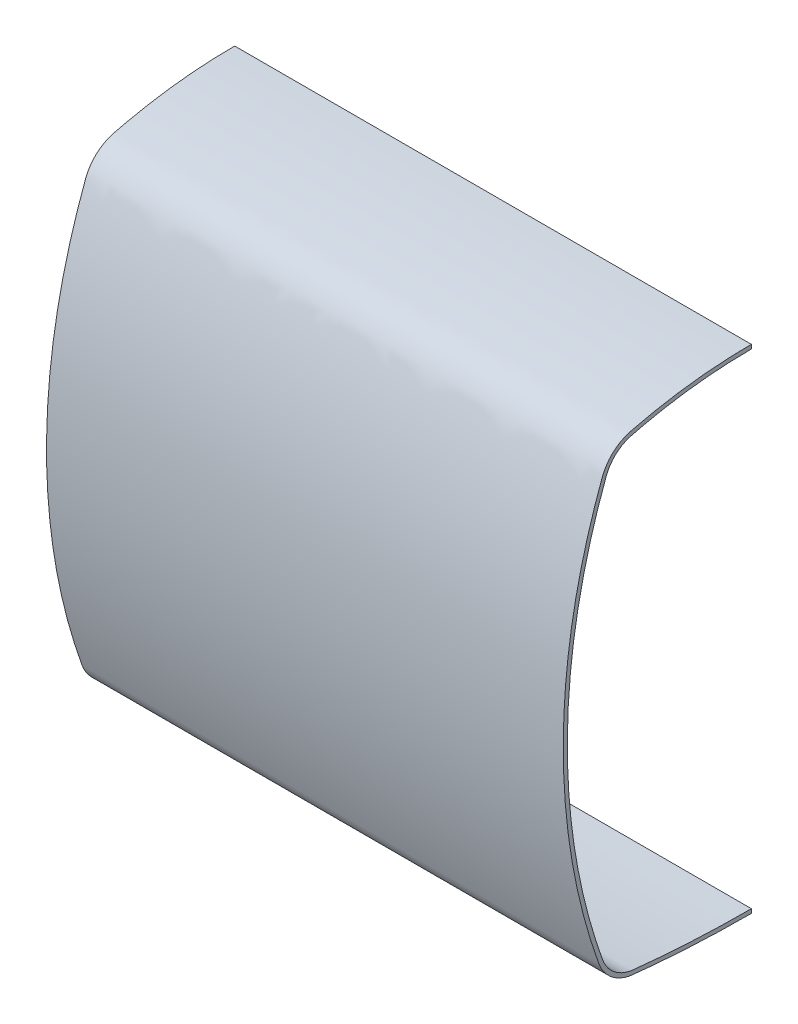
SolidWorks part; units mm, degrees
ref_plane "Front Plane" through (0, 0, 0) normal (0, 0, 1) x (1, 0, 0)
ref_plane "Top Plane" through (0, 0, 0) normal (0, 1, 0) x (1, 0, 0)
ref_plane "Right Plane" through (0, 0, 0) normal (1, 0, 0) x (0, 0, -1)
sketch "Sketch4" plane through (-245.2175, 0, 0) normal (-1, 0, 0) x (0, 0, 1)
  line L2 (-67.5, 233.8923) -> (-67.5, 231.8923)
  line L3 (-67.5, -6.3455) -> (-67.5, -8.3455)
  line L4 (-67.5, 233.8923) -> (-67.5, 231.8923)
  line L5 (-67.5, -6.3455) -> (-67.5, -8.3455)
  spline S0 degree 3 poles (1438.556, -2100.2402) (-873.6165, -475.5488) (-387.365, 299.3972) (-17.1984, 228.692) (-12.6576, 227.6897) (-8.1266, 226.5524) (-8.1092, 226.548) (-7.9319, 226.503) (-6.7443, 226.1858) (-5.5937, 225.7604) (-2.7193, 224.4334) (-0.9506, 223.251) (1.37, 221.1008) (2.0878, 220.3203) (3.3906, 218.6556) (3.9767, 217.7712) (4.7473, 216.3812) (5.1802, 215.5222) (5.5505, 214.6326) (5.7152, 214.1972) (5.7251, 214.1709) (7.4554, 209.5819) (9.06, 204.9894) (19.9636, 171.1652) (24.7754, 140.8594) (25.1771, 80.1824) (20.7669, 49.8105) (10.4386, 16.263) (9.0469, 12.073) (7.5497, 7.8792) (7.5389, 7.849) (7.3926, 7.443) (6.8573, 6.0863) (6.1793, 4.8001) (4.4911, 2.1299) (3.0868, 0.5311) (0.6314, -1.4978) (-0.2386, -2.1068) (-2.0558, -3.1763) (-3.0041, -3.6378) (-4.9622, -4.4067) (-6.4767, -4.8678) (-8.2512, -5.1848) (-8.9922, -5.2748) (-9.2233, -5.2991) (-9.2369, -5.3005) (-13.3393, -5.7303) (-17.4291, -6.1134) (-569.4844, -51.6962) (-1159.1756, 713.6096) (-1877.6478, 2288.9262) knots -2.89955 -2.89955 -2.89955 -2.89955 0.125 0.125 0.16272 0.16272 0.162842 0.162842 0.164062 0.171875 0.171875 0.1875 0.1875 0.195312 0.195312 0.203125 0.203125 0.207031 0.210205 0.210205 0.210449 0.210449 0.25 0.25 0.5 0.5 0.75 0.75 0.785889 0.785889 0.786133 0.786133 0.789062 0.796875 0.796875 0.8125 0.8125 0.820312 0.820312 0.828125 0.828125 0.835938 0.839844 0.841431 0.841431 0.841553 0.841553 0.875 0.875 5.353831 5.353831 5.353831 5.353831 only from (-67.5, 233.8923) to (-67.5, -8.3455) construction
  spline S1 degree 3 poles (-1573.5108, -2100.1852) (738.6059, -475.5313) (252.3609, 299.3964) (-117.7869, 228.6949) (-122.313, 227.6962) (-126.8734, 226.5524) (-126.9392, 226.5358) (-127.1323, 226.4858) (-128.2868, 226.1743) (-129.4063, 225.7604) (-132.2807, 224.4334) (-134.0494, 223.251) (-136.37, 221.1008) (-137.0878, 220.3203) (-138.3906, 218.6556) (-138.9767, 217.7712) (-139.7473, 216.3812) (-140.1802, 215.5222) (-140.5505, 214.6326) (-140.7152, 214.1972) (-140.7251, 214.1709) (-142.4554, 209.5819) (-144.06, 204.9894) (-154.9636, 171.1652) (-159.7754, 140.8594) (-160.1771, 80.1824) (-155.7669, 49.8105) (-145.4386, 16.263) (-144.0469, 12.073) (-142.5497, 7.8792) (-142.5389, 7.849) (-142.3926, 7.443) (-141.8573, 6.0863) (-141.1793, 4.8001) (-139.4911, 2.1299) (-138.0868, 0.5311) (-135.6314, -1.4978) (-134.7614, -2.1068) (-132.9442, -3.1763) (-131.9959, -3.6378) (-130.0378, -4.4067) (-128.5233, -4.8678) (-126.765, -5.1819) (-126.0408, -5.2708) (-125.7767, -5.2992) (-125.7184, -5.3052) (-121.601, -5.7359) (-117.5411, -6.1159) (434.4989, -51.6974) (1024.2084, 713.6501) (1742.5472, 2289.0513) knots -2.899516 -2.899516 -2.899516 -2.899516 0.125 0.125 0.162598 0.162598 0.163086 0.163086 0.164063 0.171875 0.171875 0.1875 0.1875 0.195313 0.195313 0.203125 0.203125 0.207031 0.210205 0.210205 0.210449 0.210449 0.25 0.25 0.5 0.5 0.75 0.75 0.785889 0.785889 0.786133 0.786133 0.789063 0.796875 0.796875 0.8125 0.8125 0.820313 0.820313 0.828125 0.828125 0.835938 0.839844 0.841309 0.841309 0.841797 0.841797 0.875 0.875 5.35395 5.35395 5.35395 5.35395 only from (-67.5, 233.8923) to (-67.5, -8.3455) construction
  spline S2 degree 3 poles (-67.5, 233.8923) (-52.184, 233.8923) (-32.2462, 232.0136) (-12.6576, 227.6897) (-8.1266, 226.5524) (-8.1092, 226.548) (-7.9319, 226.503) (-6.7443, 226.1858) (-5.5937, 225.7604) (-2.7193, 224.4334) (-0.9506, 223.251) (1.37, 221.1008) (2.0878, 220.3203) (3.3906, 218.6556) (3.9767, 217.7712) (4.7473, 216.3812) (5.1802, 215.5222) (5.5505, 214.6326) (5.7152, 214.1972) (5.7251, 214.1709) (7.4554, 209.5819) (9.06, 204.9894) (19.9636, 171.1652) (24.7754, 140.8594) (25.1771, 80.1824) (20.7669, 49.8105) (10.4386, 16.263) (9.0469, 12.073) (7.5497, 7.8792) (7.5389, 7.849) (7.3926, 7.443) (6.8573, 6.0863) (6.1793, 4.8001) (4.4911, 2.1299) (3.0868, 0.5311) (0.6314, -1.4978) (-0.2386, -2.1068) (-2.0558, -3.1763) (-3.0041, -3.6378) (-4.9622, -4.4067) (-6.4767, -4.8678) (-8.2512, -5.1848) (-8.9922, -5.2748) (-9.2233, -5.2991) (-9.2369, -5.3005) (-13.3393, -5.7303) (-32.7135, -7.5451) (-52.14, -8.3454) (-67.5, -8.3455) knots 0 0 0 0 0.125 0.16272 0.16272 0.162842 0.162842 0.164062 0.171875 0.171875 0.1875 0.1875 0.195312 0.195312 0.203125 0.203125 0.207031 0.210205 0.210205 0.210449 0.210449 0.25 0.25 0.5 0.5 0.75 0.75 0.785889 0.785889 0.786133 0.786133 0.789062 0.796875 0.796875 0.8125 0.8125 0.820312 0.820312 0.828125 0.828125 0.835938 0.839844 0.841431 0.841431 0.841553 0.841553 0.875 1 1 1 1
  spline S3 degree 3 poles (-67.5, 233.8923) (-82.816, 233.8923) (-102.7389, 232.015) (-122.313, 227.6962) (-126.8734, 226.5524) (-126.9392, 226.5358) (-127.1323, 226.4858) (-128.2868, 226.1743) (-129.4063, 225.7604) (-132.2807, 224.4334) (-134.0494, 223.251) (-136.37, 221.1008) (-137.0878, 220.3203) (-138.3906, 218.6556) (-138.9767, 217.7712) (-139.7473, 216.3812) (-140.1802, 215.5222) (-140.5505, 214.6326) (-140.7152, 214.1972) (-140.7251, 214.1709) (-142.4554, 209.5819) (-144.06, 204.9894) (-154.9636, 171.1652) (-159.7754, 140.8594) (-160.1771, 80.1824) (-155.7669, 49.8105) (-145.4386, 16.263) (-144.0469, 12.073) (-142.5497, 7.8792) (-142.5389, 7.849) (-142.3926, 7.443) (-141.8573, 6.0863) (-141.1793, 4.8001) (-139.4911, 2.1299) (-138.0868, 0.5311) (-135.6314, -1.4978) (-134.7614, -2.1068) (-132.9442, -3.1763) (-131.9959, -3.6378) (-130.0378, -4.4067) (-128.5233, -4.8678) (-126.765, -5.1819) (-126.0408, -5.2708) (-125.7767, -5.2992) (-125.7184, -5.3052) (-121.601, -5.7359) (-102.2566, -7.5463) (-82.86, -8.3454) (-67.5, -8.3455) knots 0 0 0 0 0.125 0.162598 0.162598 0.163086 0.163086 0.164063 0.171875 0.171875 0.1875 0.1875 0.195313 0.195313 0.203125 0.203125 0.207031 0.210205 0.210205 0.210449 0.210449 0.25 0.25 0.5 0.5 0.75 0.75 0.785889 0.785889 0.786133 0.786133 0.789063 0.796875 0.796875 0.8125 0.8125 0.820313 0.820313 0.828125 0.828125 0.835938 0.839844 0.841309 0.841309 0.841797 0.841797 0.875 1 1 1 1
  spline S6 degree 3 poles (-2273.9928, 3207.122) (-1370.3778, 1011.6613) (-662.54, -66.5403) (-13.3393, -5.7303) (-9.2369, -5.3005) (-9.2233, -5.2991) (-8.9922, -5.2748) (-8.2512, -5.1848) (-6.4767, -4.8678) (-4.9622, -4.4067) (-3.0041, -3.6378) (-2.0558, -3.1763) (-0.2386, -2.1068) (0.6314, -1.4978) (3.0868, 0.5311) (4.4911, 2.1299) (6.1793, 4.8001) (6.8573, 6.0863) (7.3926, 7.443) (7.5389, 7.849) (7.5497, 7.8792) (9.0469, 12.073) (10.4386, 16.263) (20.7669, 49.8105) (25.1771, 80.1824) (24.7754, 140.8594) (19.9636, 171.1652) (9.06, 204.9894) (7.4554, 209.5819) (5.7251, 214.1709) (5.7152, 214.1972) (5.5505, 214.6326) (5.1802, 215.5222) (4.7473, 216.3812) (3.9767, 217.7712) (3.3906, 218.6556) (2.0878, 220.3203) (1.37, 221.1008) (-0.9506, 223.251) (-2.7193, 224.4334) (-5.5937, 225.7604) (-6.7443, 226.1858) (-7.9319, 226.503) (-8.1092, 226.548) (-8.1266, 226.5524) (-12.6576, 227.6897) (-420.0375, 317.6122) (-978.4462, -650.0018) (2275.0754, -2647.6814) knots -5.150878 -5.150878 -5.150878 -5.150878 0.125 0.158447 0.158447 0.158569 0.158569 0.160156 0.164062 0.171875 0.171875 0.179688 0.179688 0.1875 0.1875 0.203125 0.203125 0.210938 0.213867 0.213867 0.214111 0.214111 0.25 0.25 0.5 0.5 0.75 0.75 0.789551 0.789551 0.789795 0.789795 0.792969 0.796875 0.796875 0.804688 0.804688 0.8125 0.8125 0.828125 0.828125 0.835938 0.837158 0.837158 0.83728 0.83728 0.875 4.22133 4.22133 4.22133 4.22133 only from (-67.5, -8.3455) to (-67.5, 233.8923)
  spline S7 degree 3 poles (2288.4799, -2641.0408) (-1011.5831, -629.3975) (-411.9913, 325.8434) (-5.3275, 223.7904) (-0.172, 220.7752) (2.9851, 215.7717) (28.7207, 147.564) (29.3678, 74.9209) (4.5498, 5.4204) (2.5953, 2.6674) (-2.6862, -1.5955) (-5.9625, -2.9489) (-655.983, -71.0558) (-1359.1239, 995.5659) (-2317.5302, 3185.4522) knots -3.233868 -3.233868 -3.233868 -3.233868 0.162725 0.162725 0.190497 0.210236 0.210236 0.785999 0.785999 0.813067 0.813067 0.841436 0.841436 6.151058 6.151058 6.151058 6.151058 only from (-67.5, 231.8923) to (-67.5, -6.3455)
  spline S8 degree 3 poles (-67.5, -8.3455) (-52.14, -8.3454) (-32.7135, -7.5451) (-13.3393, -5.7303) (-9.2369, -5.3005) (-9.2233, -5.2991) (-8.9922, -5.2748) (-8.2512, -5.1848) (-6.4767, -4.8678) (-4.9622, -4.4067) (-3.0041, -3.6378) (-2.0558, -3.1763) (-0.2386, -2.1068) (0.6314, -1.4978) (3.0868, 0.5311) (4.4911, 2.1299) (6.1793, 4.8001) (6.8573, 6.0863) (7.3926, 7.443) (7.5389, 7.849) (7.5497, 7.8792) (9.0469, 12.073) (10.4386, 16.263) (20.7669, 49.8105) (25.1771, 80.1824) (24.7754, 140.8594) (19.9636, 171.1652) (9.06, 204.9894) (7.4554, 209.5819) (5.7251, 214.1709) (5.7152, 214.1972) (5.5505, 214.6326) (5.1802, 215.5222) (4.7473, 216.3812) (3.9767, 217.7712) (3.3906, 218.6556) (2.0878, 220.3203) (1.37, 221.1008) (-0.9506, 223.251) (-2.7193, 224.4334) (-5.5937, 225.7604) (-6.7443, 226.1858) (-7.9319, 226.503) (-8.1092, 226.548) (-8.1266, 226.5524) (-12.6576, 227.6897) (-32.2462, 232.0136) (-52.184, 233.8923) (-67.5, 233.8923) knots 0 0 0 0 0.125 0.158447 0.158447 0.158569 0.158569 0.160156 0.164062 0.171875 0.171875 0.179688 0.179688 0.1875 0.1875 0.203125 0.203125 0.210938 0.213867 0.213867 0.214111 0.214111 0.25 0.25 0.5 0.5 0.75 0.75 0.789551 0.789551 0.789795 0.789795 0.792969 0.796875 0.796875 0.804688 0.804688 0.8125 0.8125 0.828125 0.828125 0.835938 0.837158 0.837158 0.83728 0.83728 0.875 1 1 1 1
  spline S9 degree 3 poles (-67.5, 231.8923) (-47.7251, 231.8923) (-27.9502, 229.4676) (-5.3275, 223.7904) (-0.172, 220.7752) (2.9851, 215.7717) (28.7207, 147.564) (29.3678, 74.9209) (4.5498, 5.4204) (2.5953, 2.6674) (-2.6862, -1.5955) (-5.9625, -2.9489) (-28.7258, -5.334) (-48.085, -6.3454) (-67.5, -6.3455) knots 0 0 0 0 0.162725 0.162725 0.190497 0.210236 0.210236 0.785999 0.785999 0.813067 0.813067 0.841436 0.841436 1 1 1 1
  dimension "D1" = 0
extrude "Boss-Extrude1" add sketch "Sketch4" against normal blind 254 contours L4 S9 L5 S2
